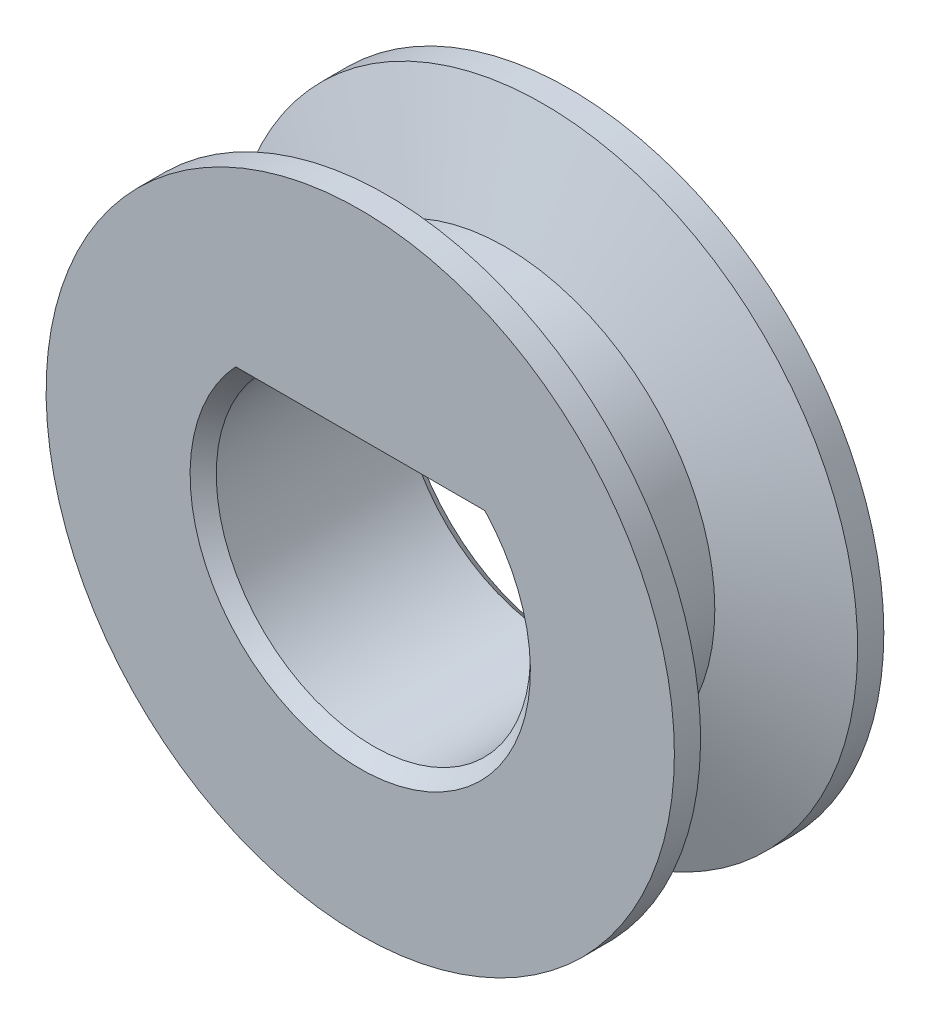
SolidWorks part; units mm, degrees
material "6061-T6 (SS)"
ref_plane "Front Plane" through (0, 0, 0) normal (0, 0, 1) x (1, 0, 0)
ref_plane "Top Plane" through (0, 0, 0) normal (0, 1, 0) x (1, 0, 0)
ref_plane "Right Plane" through (0, 0, 0) normal (1, 0, 0) x (0, 0, -1)
sketch "Sketch1" plane through (0, 0, 0) normal (0, 0, 1) x (1, 0, 0)
  circle A0 centre (0, 0) radius 19.05
  circle A1 centre (0, 0) radius 9.525
  dimension "D1" = 38.1
  dimension "D2" = 19.05
extrude "Extrude1" add sketch "Sketch1" along normal mid plane 12.7
sketch "Sketch2" plane through (0, 0, 0) normal (1, 0, 0) x (0, 0, -1)
  line L0 (-4.7625, 19.05) -> (4.7625, 19.05)
  line L2 (4.7625, 19.05) -> (2.4513, 12.7)
  line L3 (2.4513, 12.7) -> (-2.4513, 12.7)
  line L4 (-2.4513, 12.7) -> (-4.7625, 19.05)
  line L5 (-6.35, 0) -> (6.35, 0) construction
  line L6 (-6.35, 19.05) -> (-6.35, -19.05) construction
  line L7 (6.35, -19.05) -> (6.35, 19.05) construction
  point P2 (0, 19.05)
  point P5 (0, 12.7)
  dimension "D1" = 19.05
  dimension "D2" = 6.35
  dimension "D3" = 9.525
  dimension "D4" = 40
chamfer "Chamfer1" distance 0.7937 angle 45 2 edges at (9.525, 0, -6.35) (9.525, 0, 6.35)
revolve "Cut-Revolve1" cut sketch "Sketch2" angle 360 about L5
sketch "Sketch3" plane through (0, 0, -6.35) normal (0, 0, -1) x (-1, 0, 0)
  line L0 (0, 0) -> (0, 9.525) construction
  line L5 (-7.5582, 7.025) -> (7.5582, 7.025)
  circle A1 centre (0, 0) radius 10.3188 construction
  circle A2 centre (0, 0) radius 9.525 construction
  arc A3 (-7.5582, 7.025) -> (7.5582, 7.025) centre (0, 0) cw
  dimension "D1" = 2.5
extrude "Boss-Extrude1" add sketch "Sketch3" against normal through all
